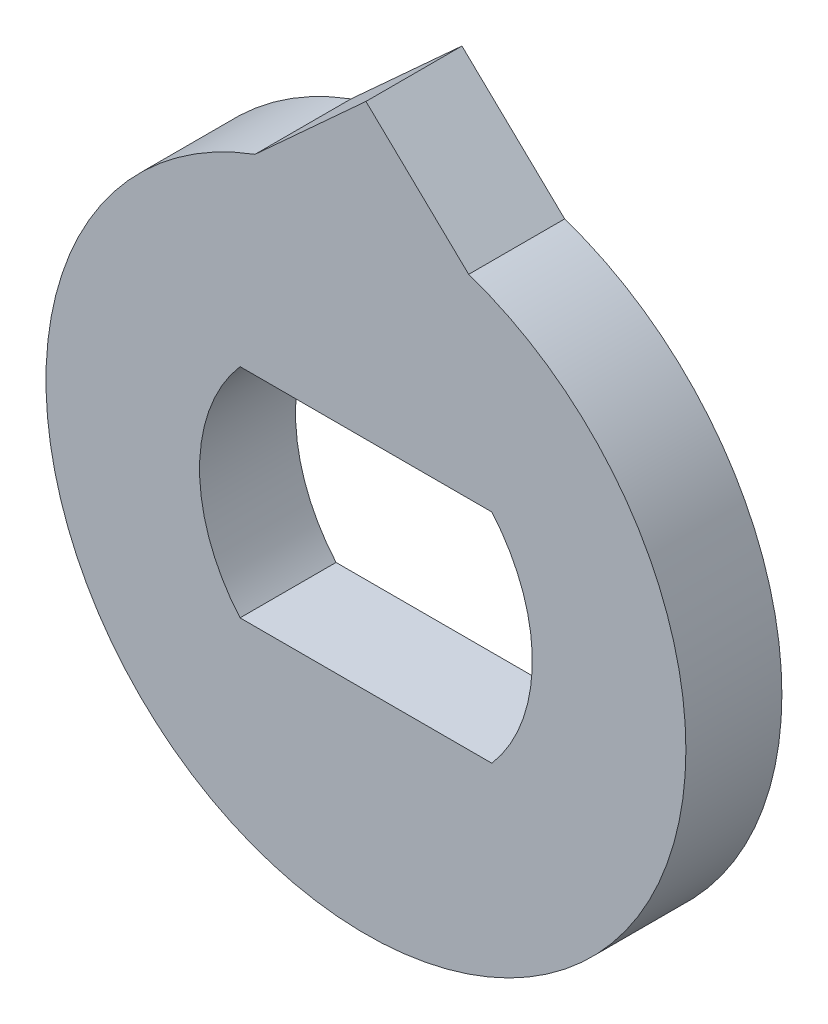
SolidWorks part; units mm, degrees
ref_plane "Front Plane" through (0, 0, 0) normal (0, 0, 1) x (1, 0, 0)
ref_plane "Top Plane" through (0, 0, 0) normal (0, 1, 0) x (1, 0, 0)
ref_plane "Right Plane" through (0, 0, 0) normal (1, 0, 0) x (0, 0, -1)
sketch "Sketch1" plane through (0, 0, 0) normal (0, 0, 1) x (1, 0, 0)
  line L0 (-1.7336, 4.6898) -> (0, 6.2726)
  line L1 (0, 6.2726) -> (1.6055, 4.7352)
  line L3 (-3.0272, 1.7) -> (3.0272, 1.7)
  line L4 (-3.0272, 1.7) -> (-3.0272, -1.7)
  line L5 (-3.0272, -1.7) -> (3.0272, -1.7)
  line L6 (3.0272, 1.7) -> (3.0272, -1.7)
  line L7 (-3.0272, 1.7) -> (3.0272, -1.7) construction
  line L8 (-3.0272, -1.7) -> (3.0272, 1.7) construction
  circle A0 centre (0, 0) radius 2.6
  circle A1 centre (0, 0) radius 5
  point P6 (0, 6.2726)
  dimension "D1" = 5.2
  dimension "D2" = 10
  dimension "D3" = 1.7
extrude "Boss-Extrude1" add sketch "Sketch1" along normal blind 1.5 contours A1 A0 | A0 L3 L4 L5 | L3 A0 | A0 L5 L6 L3 | L5 A0 | A1 L1 L0
